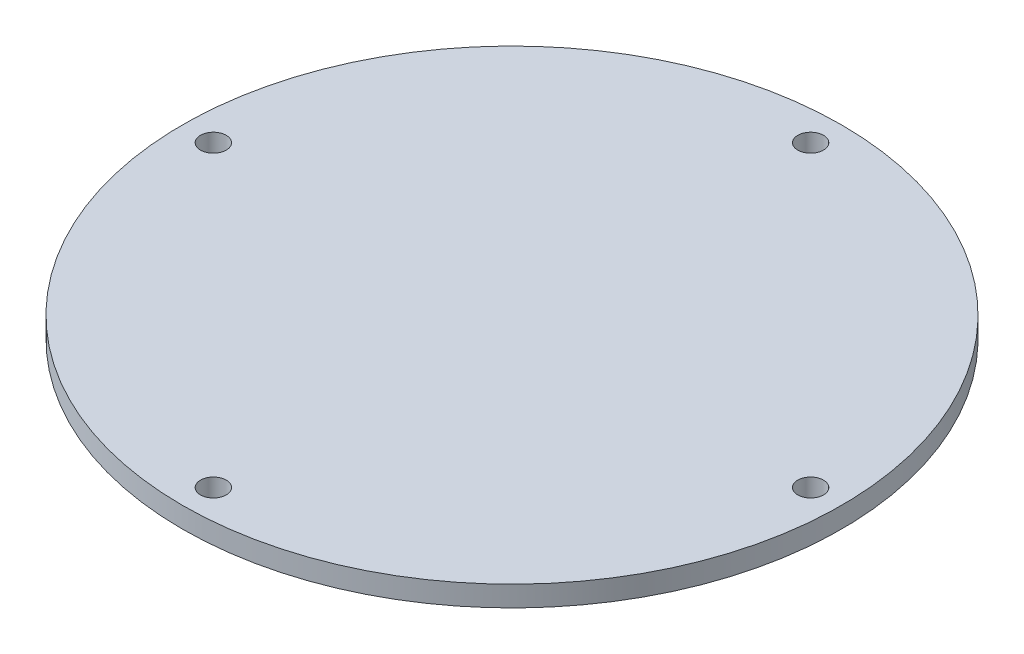
SolidWorks part; units mm, degrees
ref_plane "Front Plane" through (0, 0, 0) normal (0, 0, 1) x (1, 0, 0)
ref_plane "Top Plane" through (0, 0, 0) normal (0, 1, 0) x (1, 0, 0)
ref_plane "Right Plane" through (0, 0, 0) normal (1, 0, 0) x (0, 0, -1)
sketch "Sketch1" plane through (0, 0, 0) normal (0, 1, 0) x (1, 0, 0)
  line L0 (0, 46.0328) -> (0, -46.0328) construction
  line L1 (-46.0328, 0) -> (46.0328, 0) construction
  line L6 (-46.0328, 0) -> (0, 46.0328) construction
  line L7 (0, 46.0328) -> (46.0328, 0) construction
  line L8 (46.0328, 0) -> (0, -46.0328) construction
  line L9 (0, -46.0328) -> (-46.0328, 0) construction
  circle A4 centre (0, 0) radius 50.8
  circle A5 centre (0, 46.0328) radius 1.9844
  circle A6 centre (46.0328, 0) radius 1.9844
  circle A7 centre (0, -46.0328) radius 1.9844
  circle A8 centre (-46.0328, 0) radius 1.9844
  dimension "D1" = 101.6
extrude "Boss-Extrude1" add sketch "Sketch1" along normal blind 3.175
